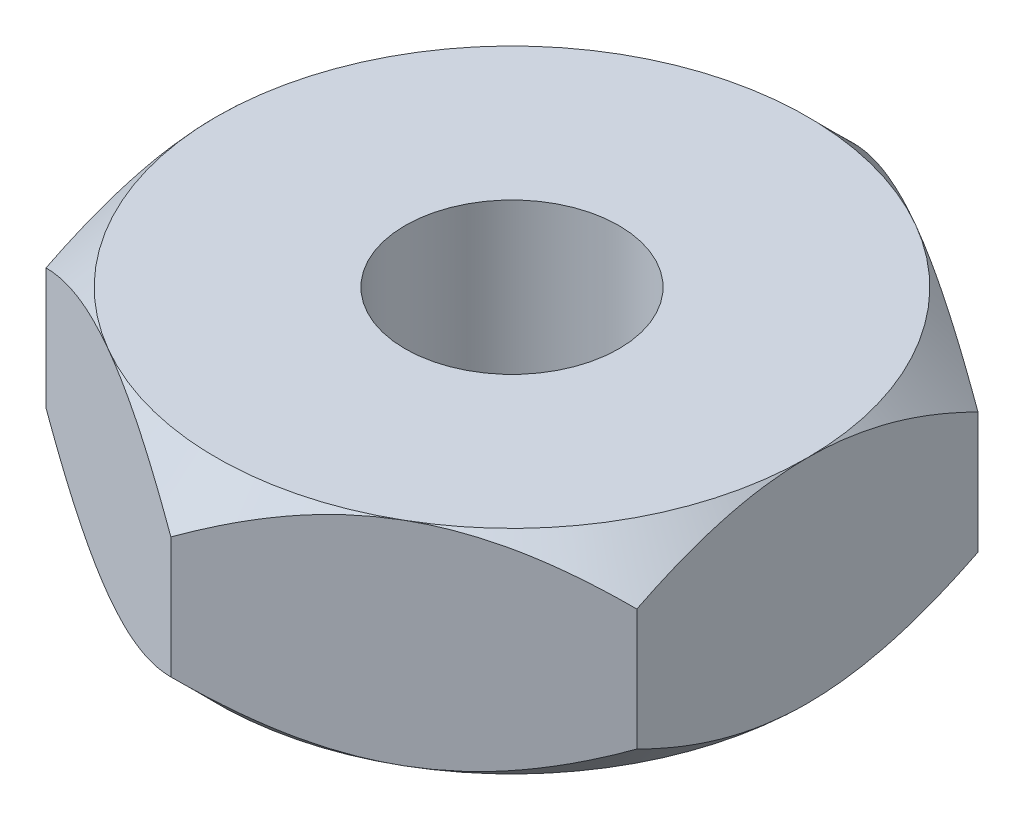
SolidWorks part; units mm, degrees
ref_plane "Front Plane" through (0, 0, 0) normal (0, 0, 1) x (1, 0, 0)
ref_plane "Top Plane" through (0, 0, 0) normal (0, 1, 0) x (1, 0, 0)
ref_plane "Right Plane" through (0, 0, 0) normal (1, 0, 0) x (0, 0, -1)
sketch "Sketch1" plane through (0, 0, 0) normal (0, 1, 0) x (1, 0, 0)
  line L1 (0, 3.6084) -> (-3.125, 1.8042)
  line L2 (-3.125, 1.8042) -> (-3.125, -1.8042)
  line L3 (-3.125, -1.8042) -> (0, -3.6084)
  line L4 (0, -3.6084) -> (3.125, -1.8042)
  line L5 (3.125, -1.8042) -> (3.125, 1.8042)
  line L6 (3.125, 1.8042) -> (0, 3.6084)
  circle A0 centre (0, 0) radius 3.125 construction
  dimension "D1" = 6.25
extrude "Boss-Extrude1" add sketch "Sketch1" along normal mid plane 2.25 contours L1 L2 L3 L4 L5 L6
sketch "Sketch2" plane through (0, 0, 0) normal (0, 0, 1) x (1, 0, 0)
  line L0 (-3.125, 1.125) -> (0, 4.25) construction
  line L1 (0, 4.25) -> (-4.25, 4.25) construction
  line L2 (-4.25, 1.125) -> (-4.25, 0)
  line L3 (-4.25, 0) -> (-3.125, 1.125)
  line L4 (-3.125, 1.125) -> (-3.125, -1.125) construction
  line L6 (0, 4.25) -> (0, 1.125) construction
  line L7 (-3.125, 1.125) -> (-4.25, 1.125)
  point P3 (-3.125, 0)
  dimension "D1" = 45
revolve "Cut-Revolve2" cut sketch "Sketch2" angle 360 about L6
mirror "Mirror1" about plane through (0, 0, 0) normal (0, 1, 0) of "Cut-Revolve2"
hole_wizard "#4-40 Tapped Hole1" positions "Sketch4" profile "Sketch3" tap size "#4-40" standard "ANSI Inch"
sketch "Sketch4" plane through (0, 1.125, 0) normal (0, 1, 0) x (1, 0, 0)
  point P0 (0, 0)
sketch "Sketch3" plane through (0, 1.125, 0) normal (1, 0, 0) x (0, 0, 1)
  line L0 (0, 0) -> (0, 9.5492)
  line L1 (0, 9.5492) -> (1.1303, 8.87)
  line L2 (1.1303, 8.87) -> (1.1303, 0)
  line L5 (1.1303, 0) -> (0, 0)
  line L10 (0, 9.5492) -> (-1.1303, 8.87) construction
  line L11 (0, -6.35) -> (0, 107.95) construction
  dimension "Tap Drill Dia." = 2.2606
  dimension "Tap Drill Depth" = 8.87
  dimension "Drill Angle" = 118
cosmetic thread "Hole Thread1" parameters "D1"=2.25, "D2"=2.8448
